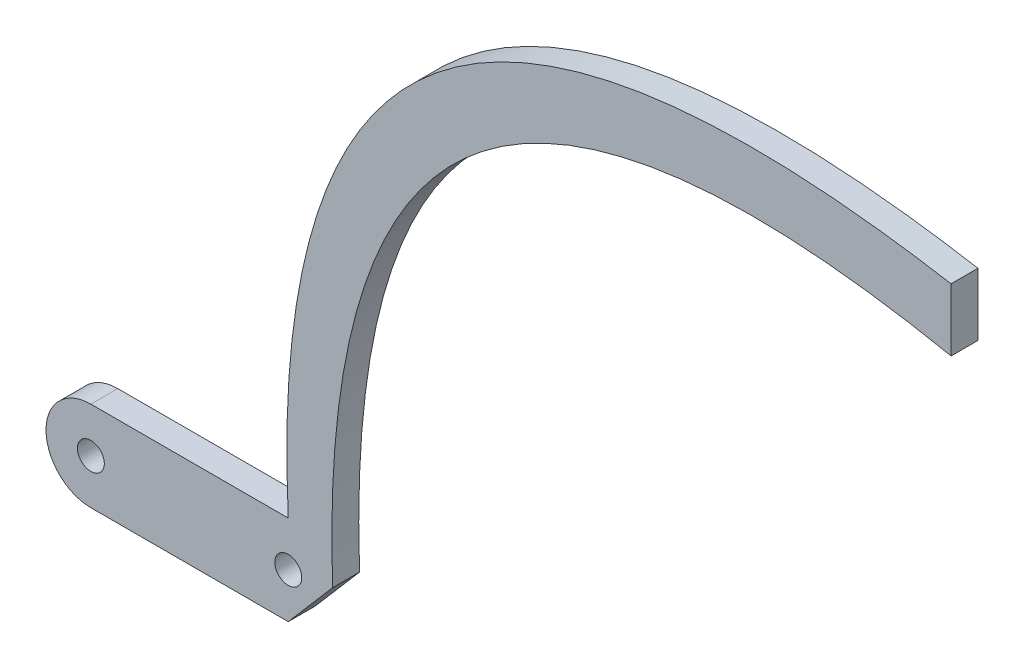
SolidWorks part; units mm, degrees
ref_plane "Front Plane" through (0, 0, 0) normal (0, 0, 1) x (1, 0, 0)
ref_plane "Top Plane" through (0, 0, 0) normal (0, 1, 0) x (1, 0, 0)
ref_plane "Right Plane" through (0, 0, 0) normal (1, 0, 0) x (0, 0, -1)
sketch "Sketch1" plane through (0, 0, 0) normal (0, 0, 1) x (1, 0, 0)
  line L0 (0, 0) -> (22, 0) construction
  line L1 (0, 5) -> (22, 5)
  line L2 (0, -5) -> (22, -5)
  line L3 (20.05, 5) -> (26.9433, 0.7509) construction
  line L4 (95.8755, 64.5505) -> (95.8755, 57.5844)
  line L24 (26.9433, 0.7509) -> (22, -5)
  arc A0 (0, 5) -> (0, -5) centre (0, 0) ccw
  arc A1 (22, -5) -> (22, 5) centre (22, 0) ccw
  circle A2 centre (0, 0) radius 1.5
  circle A3 centre (22, 0) radius 1.5
  spline S0 degree 2 poles (22, 5) (18.376, 77.9406) (95.8755, 64.5505) knots 0 0 0 1 1 1
  spline S1 degree 2 poles (26.9433, 0.7509) (24.3794, 72.0753) (95.8755, 57.5844) knots 0 0 0 1 1 1
  point P3 (11, 0)
  point P12 (114.3053, 26.5905)
  point P13 (61.4182, 40.19)
  point P14 (57.9643, 46.0184)
  point P15 (112.7942, 33.714)
  point P16 (114.0894, 25.2953)
  point P17 (44.7193, 48.4826)
  point P21 (102.5907, 31.1033)
  point P22 (106.1956, 59.6484)
  point P24 (102.8416, 52.4244)
  point P26 (49.693, 54.7464)
  point P28 (43.2429, 50.8763)
  point P29 (43.2429, 59.3904)
  point P30 (47.887, 54.2304)
  point P33 (49.951, 60.9384)
  point P34 (0, 0)
  point P35 (96.1335, 64.5505)
  point P36 (34.4708, 52.4244)
  point P37 (41.6949, 49.5863)
  point P38 (95.8755, 57.5844)
  dimension "D2" = 10
  dimension "D11" = 3
  dimension "D1" = 22
  dimension "D4" = 1.95
extrude "Boss-Extrude1" add sketch "Sketch1" along normal blind 3
